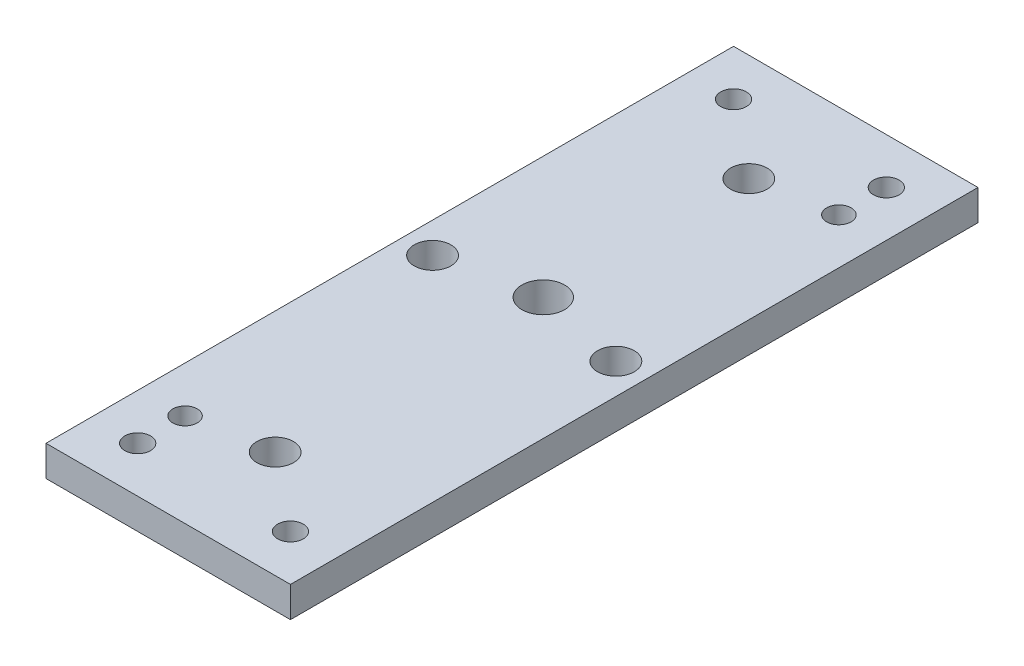
SolidWorks part; units mm, degrees
material "K110"
ref_plane "Front Plane" through (0, 0, 0) normal (0, 0, 1) x (1, 0, 0)
ref_plane "Top Plane" through (0, 0, 0) normal (0, 1, 0) x (1, 0, 0)
ref_plane "Right Plane" through (0, 0, 0) normal (1, 0, 0) x (0, 0, -1)
sketch "Sketch1" plane through (0, 0, 0) normal (0, 1, 0) x (1, 0, 0)
  line L1 (-40, -112.5) -> (40, -112.5)
  line L2 (-40, -112.5) -> (-40, 112.5)
  line L3 (-40, 112.5) -> (40, 112.5)
  line L4 (40, -112.5) -> (40, 112.5)
  line L5 (-40, -112.5) -> (40, 112.5) construction
  line L6 (-40, 112.5) -> (40, -112.5) construction
  point P0 (0, 0)
  dimension "D1" = 225
  dimension "D2" = 80
extrude "Boss-Extrude1" add sketch "Sketch1" against normal blind 10
sketch "Sketch2" plane through (0, 0, 0) normal (0, 1, 0) x (1, 0, 0)
  circle A0 centre (0, 77.5) radius 6 construction
  circle A1 centre (30, 4) radius 6 construction
  circle A2 centre (-30, 4) radius 6 construction
  circle A3 centre (0, -77.5) radius 6 construction
  circle A4 centre (0, 77.5) radius 6
  circle A5 centre (30, 4) radius 6
  circle A6 centre (-30, 4) radius 6
  circle A7 centre (0, -77.5) radius 6
extrude "Cut-Extrude1" cut sketch "Sketch2" against normal up to next
hole_wizard "M8 Clearance Hole1" positions "Sketch6" profile "Sketch5" hole size "M8" standard "ISO" end condition through all
sketch "Sketch6" plane through (0, 0, 0) normal (0, 1, 0) x (1, 0, 0)
  point P0 (-25, 97.5)
  point P3 (25, 97.5)
  point P6 (25, -97.5)
  point P9 (-25, -97.5)
sketch "Sketch5" plane through (-25, 0, -97.5) normal (1, 0, 0) x (0, 0, 1)
  line L0 (0, 0) -> (0, 10)
  line L1 (0, 10) -> (4.2, 10)
  line L2 (4.2, 10) -> (4.2, 0)
  line L5 (4.2, 0) -> (0, 0)
  line L11 (0, -6.35) -> (0, 107.95) construction
  dimension "Thru Hole Dia." = 8.4
  dimension "Thru Hole Depth" = 10
hole_wizard "Ø8.0mm Dowel Hole1" positions "Sketch9" profile "Sketch8" hole size "Ø8.0" standard "ISO" end condition through all
sketch "Sketch9" plane through (0, 0, 0) normal (0, 1, 0) x (1, 0, 0)
  point P0 (25, 81.975)
  point P3 (-25, -82)
sketch "Sketch8" plane through (25, 0, -81.975) normal (1, 0, 0) x (0, 0, 1)
  line L0 (0, 0) -> (0, 10)
  line L1 (0, 10) -> (4, 10)
  line L2 (4, 10) -> (4, 0)
  line L5 (4, 0) -> (0, 0)
  line L11 (0, -6.35) -> (0, 107.95) construction
  dimension "Thru Hole Dia." = 8
  dimension "Thru Hole Depth" = 10
sketch "Sketch10" plane through (0, 0, 0) normal (0, 1, 0) x (1, 0, 0)
  circle A0 centre (0, 10.23) radius 7 construction
  circle A1 centre (0, 10.23) radius 7
extrude "Cut-Extrude3" cut sketch "Sketch10" against normal up to next
